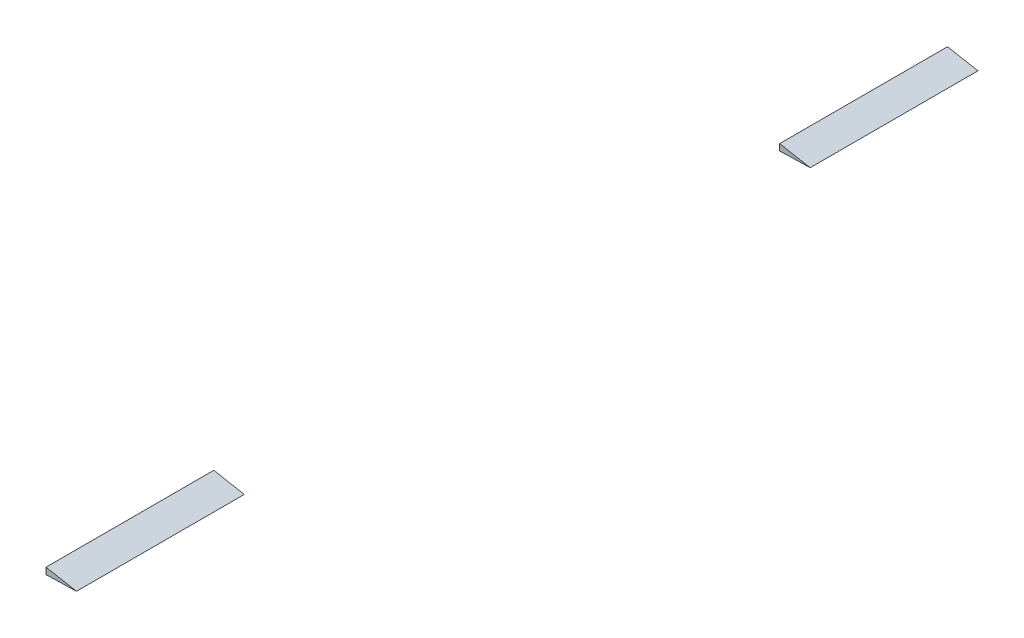
SolidWorks part; units mm, degrees
ref_plane "Front Plane" through (0, 0, 0) normal (0, 0, 1) x (1, 0, 0)
ref_plane "Top Plane" through (0, 0, 0) normal (0, 1, 0) x (1, 0, 0)
ref_plane "Right Plane" through (0, 0, 0) normal (1, 0, 0) x (0, 0, -1)
sketch "Sketch1" plane through (0, 0, 0) normal (0, 0, 1) x (1, 0, 0)
  spline S0 degree 3 poles (100.086, -5.734) (101.1259, -5.7095) (100.1039, -5.6235) (99.2806, -5.4646) (97.3018, -5.1673) (94.8938, -4.7403) (91.7634, -4.194) (88.0758, -3.5271) (83.8259, -2.7338) (79.0747, -1.8292) (73.8683, -0.8153) (68.2576, 0.2815) (62.2977, 1.4477) (56.0406, 2.6595) (49.5223, 3.8633) (42.7762, 5.0242) (35.8425, 6.1594) (28.7549, 7.2252) (21.5571, 8.212) (14.2899, 9.117) (6.9865, 9.8965) (-0.3123, 10.5674) (-7.5733, 11.1015) (-14.7568, 11.4845) (-21.8292, 11.7343) (-28.7564, 11.821) (-35.5035, 11.7506) (-42.0399, 11.5281) (-48.3376, 11.1397) (-54.3688, 10.5993) (-60.1078, 9.9161) (-65.5246, 9.0828) (-70.6007, 8.1336) (-75.3121, 7.0603) (-79.639, 5.8824) (-83.5658, 4.6206) (-87.0746, 3.2865) (-90.1553, 1.9084) (-92.7948, 0.5046) (-94.9831, -0.9044) (-96.7129, -2.2702) (-98.0005, -3.5808) (-98.7619, -4.7432) (-99.2301, -5.8582) (-98.606, -6.8701) (-97.4444, -7.5453) (-95.7467, -8.1886) (-93.4449, -8.653) (-90.5328, -8.9818) (-87.0128, -9.2499) (-82.9066, -9.4712) (-78.2402, -9.5911) (-73.0476, -9.7) (-67.3645, -9.7268) (-61.2329, -9.7356) (-54.6956, -9.664) (-47.7879, -9.5741) (-40.5477, -9.3999) (-33.0149, -9.2242) (-25.2415, -9.0244) (-17.2818, -8.802) (-9.1941, -8.5755) (-1.0348, -8.3896) (7.1349, -8.1639) (15.2619, -7.9372) (23.292, -7.7533) (31.172, -7.5204) (38.8533, -7.3203) (46.2827, -7.155) (53.3967, -6.9428) (60.1348, -6.7644) (66.4618, -6.6108) (72.37, -6.4441) (77.8517, -6.3047) (82.8703, -6.1895) (87.373, -6.0742) (91.2866, -5.9437) (94.6106, -5.8638) (97.1585, -5.8207) (99.2315, -5.7383) (100.086, -5.734) (101.1259, -5.7095) (100.1039, -5.6235) knots -0.008528 -0.003816 -0.00096 0 0.000951 0.003757 0.008317 0.014522 0.022293 0.03156 0.042221 0.054151 0.067231 0.081331 0.096307 0.112012 0.128327 0.145184 0.162488 0.180136 0.198033 0.216059 0.234134 0.252192 0.270104 0.287817 0.305235 0.322284 0.338896 0.354986 0.370506 0.385417 0.399632 0.413116 0.425823 0.437704 0.448737 0.45888 0.468105 0.476405 0.483748 0.490134 0.495557 0.500012 0.503516 0.506001 0.508215 0.511494 0.515844 0.521547 0.528755 0.537449 0.547575 0.559074 0.571867 0.585873 0.60098 0.61708 0.634081 0.651921 0.670484 0.689642 0.709259 0.729201 0.749303 0.769441 0.789466 0.809254 0.82867 0.847598 0.865915 0.883467 0.900079 0.915618 0.930135 0.943663 0.95605 0.967159 0.976853 0.984996 0.991472 0.996184 0.99904 1 1.000951 1.003757 1.008317 only from (100.9182, -5.7031) to (100.9182, -5.7031)
extrude "Boss-Extrude1" add sketch "Sketch1" along normal mid plane 1750
sketch "Sketch3" plane through (0, 0, 0) normal (0, 1, 0) x (1, 0, 0)
  line L0 (100.9182, 835.9) -> (44.3701, 835.9)
  line L2 (100.9182, 524.7075) -> (44.3701, 524.7075)
  line L3 (44.3701, 835.9) -> (44.3701, 524.7075)
  line L4 (100.9182, 875) -> (-99.0734, 875) construction
  line L5 (86.0245, 875) -> (86.5325, 875) construction
  line L8 (-6.5667, 0) -> (6.5667, 0) construction
  line L10 (100.9182, -524.7075) -> (44.3701, -524.7075)
  line L11 (44.3701, -835.9) -> (44.3701, -524.7075)
  line L12 (100.9182, -835.9) -> (44.3701, -835.9)
  line L13 (100.9182, 835.9) -> (100.9182, 941.2715)
  line L14 (100.9182, 941.2715) -> (-134.1332, 941.2715)
  line L15 (-134.1332, 941.2715) -> (-134.1332, -1428.4071)
  line L16 (-134.1332, -1428.4071) -> (100.9182, -1428.4071)
  line L17 (100.9182, -1428.4071) -> (100.9182, -835.9)
  line L18 (100.9182, -524.7075) -> (100.9182, 524.7075)
  dimension "D1" = 311.1925
  dimension "D2" = 56.5481
  dimension "D3" = 39.1
extrude "Cut-Extrude1" cut sketch "Sketch3" against normal through all both and the other way through all
